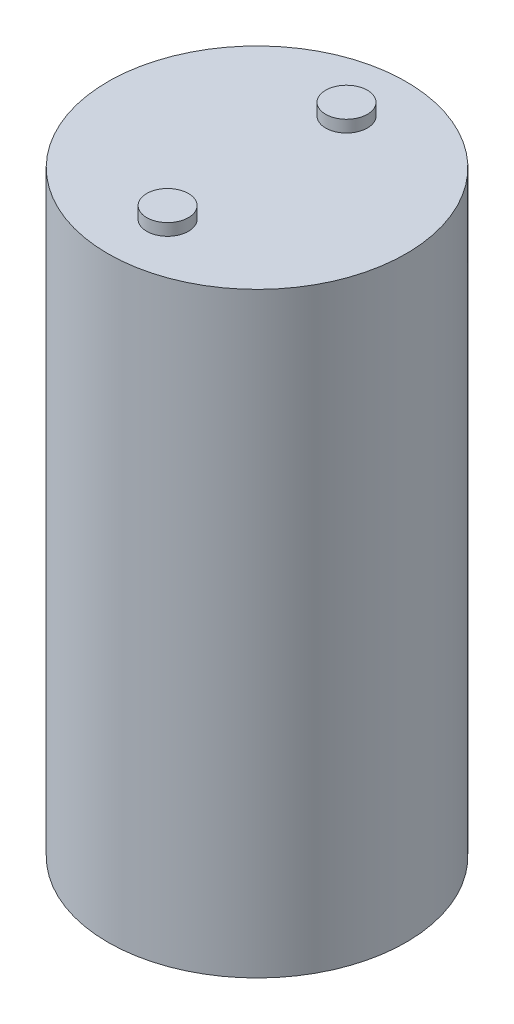
SolidWorks part; units mm, degrees
ref_plane "Front Plane" through (0, 0, 0) normal (0, 0, 1) x (1, 0, 0)
ref_plane "Top Plane" through (0, 0, 0) normal (0, 1, 0) x (1, 0, 0)
ref_plane "Right Plane" through (0, 0, 0) normal (1, 0, 0) x (0, 0, -1)
sketch "Sketch1" plane through (0, 0, 0) normal (0, 1, 0) x (1, 0, 0)
  circle A0 centre (0, 0) radius 12.5
  dimension "D1" = 25
extrude "Boss-Extrude1" add sketch "Sketch1" along normal blind 50
sketch "Sketch2" plane through (0, 50, 0) normal (0, 1, 0) x (1, 0, 0)
  line L0 (0, 7.5) -> (0, -7.5)
  circle A0 centre (0, 7.5) radius 1.75
  circle A1 centre (0, -7.5) radius 1.75
  point P4 (0, 0)
  dimension "D1" = 3.5
  dimension "D2" = 15
extrude "Boss-Extrude2" add sketch "Sketch2" along normal blind 1
